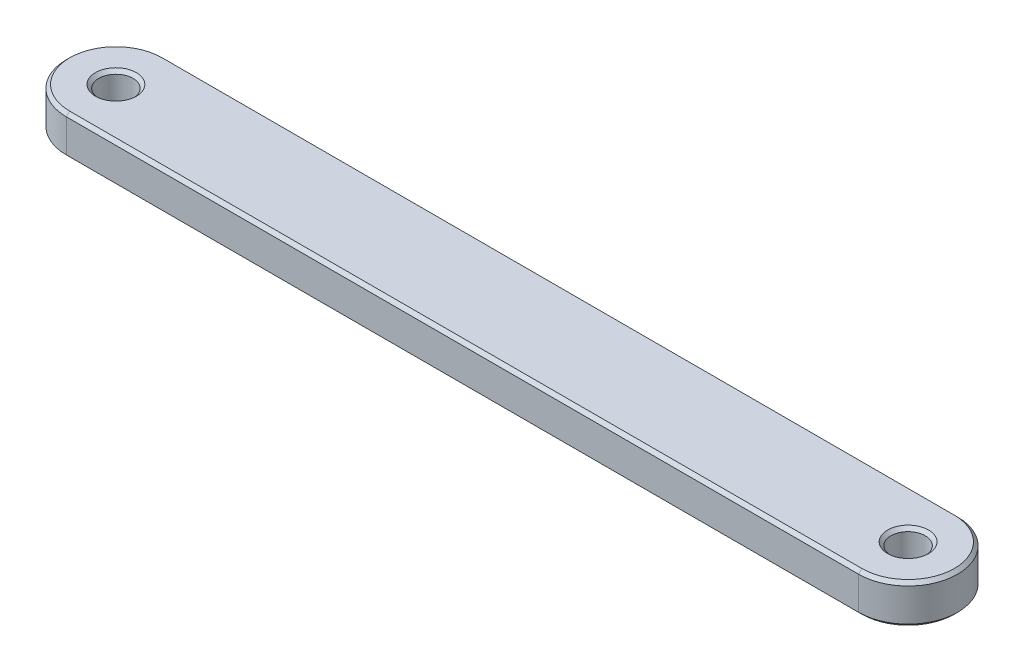
SolidWorks part; units mm, degrees
ref_plane "Front Plane" through (0, 0, 0) normal (0, 0, 1) x (1, 0, 0)
ref_plane "Top Plane" through (0, 0, 0) normal (0, 1, 0) x (1, 0, 0)
ref_plane "Right Plane" through (0, 0, 0) normal (1, 0, 0) x (0, 0, -1)
sketch "Sketch1" plane through (0, 0, 0) normal (0, 1, 0) x (1, 0, 0)
  line L0 (0, 0) -> (120, 0) construction
  line L1 (0, 0) -> (120, 0) construction
  line L2 (0, 7.5) -> (120, 7.5)
  line L3 (0, -7.5) -> (120, -7.5)
  circle A0 centre (0, 0) radius 2.6
  circle A1 centre (120, 0) radius 2.6
  arc A2 (0, 7.5) -> (0, -7.5) centre (0, 0) ccw
  arc A3 (120, -7.5) -> (120, 7.5) centre (120, 0) ccw
  point P5 (60, 0)
  dimension "D2" = 5.2
  dimension "D1" = 120
  dimension "D3" = 15
extrude "Boss-Extrude1" add sketch "Sketch1" along normal mid plane 6 contours L3 A3 L2 A2 A0 A1
chamfer "Chamfer1" distance 0.5 angle 45 12 edges at (127.5, -3, 0) (60, -3, -7.5) (-7.5, -3, 0) (60, -3, 7.5) (120, -3, 2.6) (0, -3, 2.6) (-7.5, 3, 0) (60, 3, -7.5) (127.5, 3, 0) (60, 3, 7.5) (120, 3, 2.6) (0, 3, 2.6)
